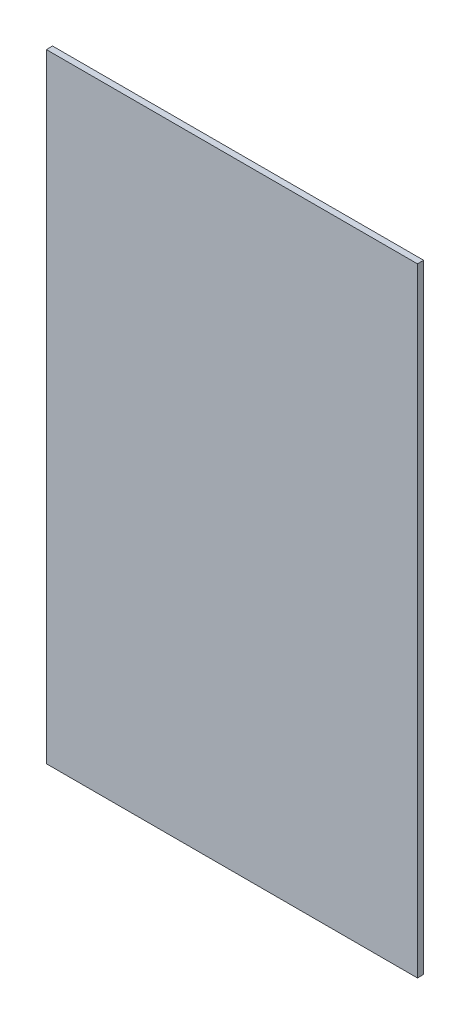
SolidWorks part; units mm, degrees
ref_plane "Ebene vorne" through (0, 0, 0) normal (0, 0, 1) x (1, 0, 0)
ref_plane "Ebene oben" through (0, 0, 0) normal (0, 1, 0) x (1, 0, 0)
ref_plane "Ebene rechts" through (0, 0, 0) normal (1, 0, 0) x (0, 0, -1)
sketch "Sketch1" plane through (0, 0, 0) normal (0, 0, 1) x (1, 0, 0)
  line L1 (-30.9627, 42.0574) -> (29.0373, 42.0574)
  line L2 (-30.9627, 42.0574) -> (-30.9627, -57.9426)
  line L3 (-30.9627, -57.9426) -> (29.0373, -57.9426)
  line L4 (29.0373, 42.0574) -> (29.0373, -57.9426)
  dimension "D1" = 60
  dimension "D2" = 100
extrude "Boss-Extrude1" add sketch "Sketch1" along normal blind 1
